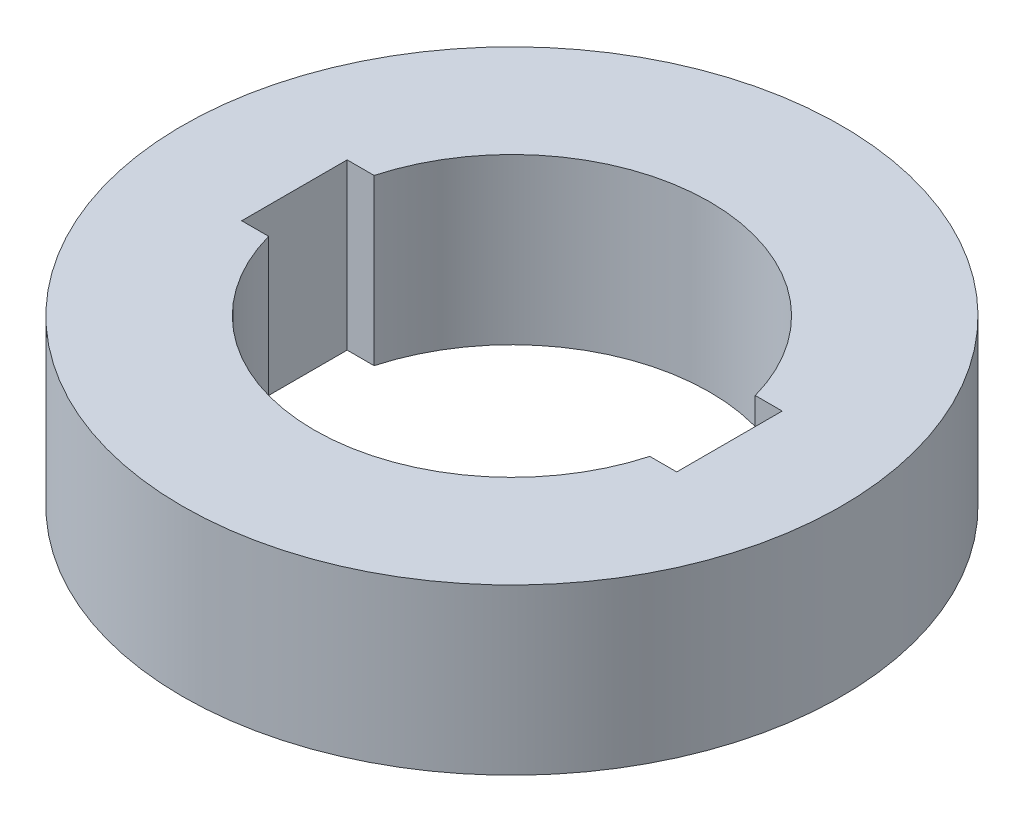
SolidWorks part; units mm, degrees
ref_plane "Front Plane" through (0, 0, 0) normal (0, 0, 1) x (1, 0, 0)
ref_plane "Top Plane" through (0, 0, 0) normal (0, 1, 0) x (1, 0, 0)
ref_plane "Right Plane" through (0, 0, 0) normal (1, 0, 0) x (0, 0, -1)
sketch "Sketch1" plane through (0, 0, 0) normal (0, 1, 0) x (1, 0, 0)
  line L0 (0, -50) -> (0, 50) construction
  line L1 (-28.9137, 8) -> (-33, 8)
  line L2 (28.9137, 8) -> (33, 8)
  line L3 (-33, 8) -> (-33, -8)
  line L4 (33, 8) -> (33, -8)
  line L5 (-33, -8) -> (-28.9137, -8)
  line L6 (33, -8) -> (28.9137, -8)
  circle A0 centre (0, 0) radius 50
  arc A1 (-28.9137, -8) -> (28.9137, -8) centre (0, 0) ccw
  arc A2 (28.9137, 8) -> (-28.9137, 8) centre (0, 0) ccw
  point P14 (-33, 0)
  point P15 (-33, 7.4461)
  dimension "D3" = 100
  dimension "D4" = 60
  dimension "D1" = 66
  dimension "D2" = 16
extrude "Boss-Extrude1" add sketch "Sketch1" along normal mid plane 25
